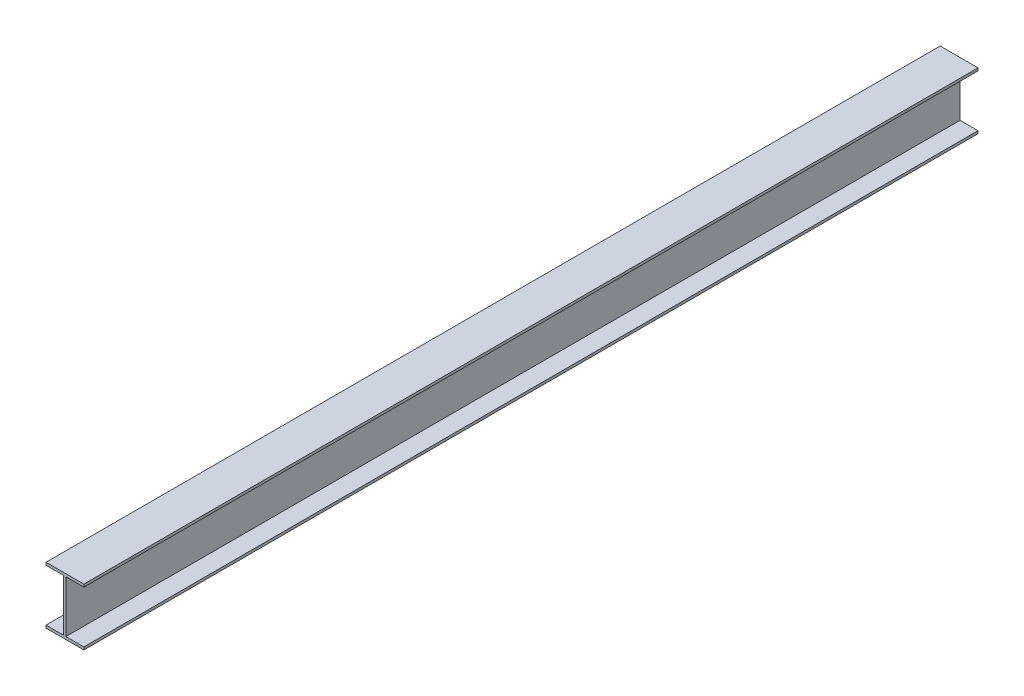
SolidWorks part; units mm, degrees
material "ASTM A992 Steel"
ref_plane "Front" through (0, 0, 0) normal (0, 0, 1) x (1, 0, 0)
ref_plane "Top" through (0, 0, 0) normal (0, 1, 0) x (1, 0, 0)
ref_plane "Right" through (0, 0, 0) normal (1, 0, 0) x (0, 0, -1)
sketch "Sketch1" plane through (0, 0, 0) normal (0, 0, 1) x (1, 0, 0)
  line L0 (0, -0.0002) -> (101.6, -0.0002)
  line L1 (101.6, -0.0002) -> (101.6, -7.1122)
  line L2 (101.6, -7.1122) -> (53.408, -7.1122)
  line L3 (53.408, -7.1122) -> (53.408, -146.0502)
  line L4 (53.408, -146.0502) -> (101.6, -146.0502)
  line L5 (101.6, -146.0502) -> (101.6, -153.1622)
  line L6 (101.6, -153.1622) -> (0, -153.1622)
  line L7 (0, -153.1622) -> (0, -146.0502)
  line L8 (0, -146.0502) -> (47.566, -146.0502)
  line L9 (47.566, -146.0502) -> (47.566, -7.1122)
  line L10 (47.566, -7.1122) -> (0, -7.1122)
  line L11 (0, -7.1122) -> (0, -0.0002)
  line L12 (50.8, -0.0002) -> (50.8, -153.1622) construction
  dimension "D1" = 5.842
  dimension "D2" = 7.112
  dimension "D3" = 7.112
  dimension "D4" = 7.112
  dimension "D5" = 153.162
  dimension "D6" = 50.8
  dimension "D7" = 50.8
  dimension "D8" = 47.566
extrude "Boss-Extrude1" add sketch "Sketch1" along normal blind 2400
